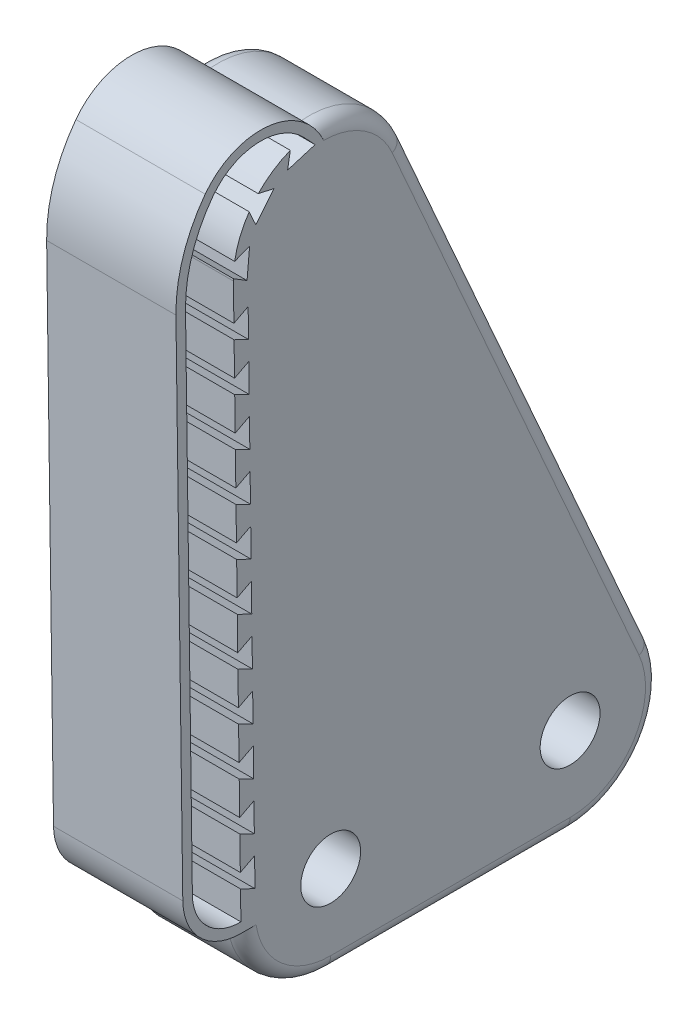
SolidWorks part; units mm, degrees
material "ABS"
ref_plane "Front" through (0, 0, 0) normal (0, 0, 1) x (1, 0, 0)
ref_plane "Top" through (0, 0, 0) normal (0, 1, 0) x (1, 0, 0)
ref_plane "Right" through (0, 0, 0) normal (1, 0, 0) x (0, 0, -1)
sketch "Sketch1" plane through (0, 0, 0) normal (1, 0, 0) x (0, 0, -1)
  line L0 (0, -4.7625) -> (12.7, -4.7625)
  line L1 (17.0561, 1.9251) -> (3.9577, 31.5642)
  line L2 (-5.1604, 29.5751) -> (-4.7621, -0.064)
  arc A0 (-4.7621, -0.064) -> (0, -4.7625) centre (0, 0) ccw
  arc A1 (12.7, -4.7625) -> (17.0561, 1.9251) centre (12.7, 0) ccw
  arc A2 (3.9577, 31.5642) -> (-5.1604, 29.5751) centre (-0.3983, 29.6391) ccw
  dimension "D1" = 4.7625
  dimension "D2" = 12.7
  dimension "D3" = 29.6418
  dimension "D4" = 90.77
extrude "Boss-Extrude1" add sketch "Sketch1" along normal blind 6.35
sketch "Sketch2" plane through (6.35, 0, 0) normal (1, 0, 0) x (0, 0, -1)
  circle A1 centre (0, 0) radius 1.5875
  circle A2 centre (12.7, 0) radius 1.5875
  dimension "D1" = 3.175
extrude "Cut-Extrude1" cut sketch "Sketch2" against normal blind 38.1
sketch "Sketch3" plane through (6.35, 0, 0) normal (1, 0, 0) x (0, 0, -1)
  line L0 (-4.7826, 1.4599) -> (-4.7928, 2.2218)
  line L1 (-5.1604, 29.5751) -> (-4.7621, -0.064) construction
  line L2 (-4.7928, 2.2218) -> (-4.036, 2.613)
  line L3 (-4.036, 2.613) -> (-4.0155, 1.0891)
  line L4 (-4.0155, 1.0891) -> (-4.7826, 1.4599)
  dimension "D1" = 0.762
  dimension "D2" = 1.524
  dimension "D3" = 0.762
  dimension "D4" = 1.524
extrude "Cut-Extrude2" cut sketch "Sketch3" against normal blind 6.35
pattern_linear "LPattern1" count 11 spacing 2.54 along (0, 0.9999, 0.0134) of "Cut-Extrude2"
sketch "Sketch5" plane through (6.35, 0, 0) normal (1, 0, 0) x (0, 0, -1)
  line L0 (-2.1425, 34.0708) -> (-2.2856, 33.2309)
  line L1 (-2.2856, 33.2309) -> (-0.8274, 33.6738)
  line L2 (-0.8274, 33.6738) -> (-1.4134, 34.2922)
  line L3 (-2.1425, 34.0708) -> (-1.4134, 34.2922) construction
  arc A0 (3.9577, 31.5642) -> (-5.1604, 29.5751) centre (-0.3983, 29.6391) ccw construction
  arc A1 (-2.1425, 34.0708) -> (-1.4134, 34.2922) centre (-0.3983, 29.6391) cw
  dimension "D1" = 0.762
  dimension "D2" = 1.524
  dimension "D3" = 0.762
extrude "Cut-Extrude3" cut sketch "Sketch5" against normal blind 6.35
pattern_circular "CirPattern1" count 3 every 34 about axis through (0, 29.6391, 0.3983) along (1, 0, 0) of "Cut-Extrude3"
sketch "Sketch6" plane through (0, 0, 0) normal (1, 0, 0) x (0, 0, -1)
  line L0 (0, 0) -> (-4.7621, -0.064) construction
  line L1 (-7.336, 2.4416) -> (-7.7002, 29.541)
  line L2 (-0.8274, 33.6738) -> (-1.4134, 34.2922) construction
  line L3 (-8.2081, 29.5342) -> (-7.844, 2.4416)
  line L4 (-4.7621, -0.5992) -> (-4.7247, -0.5992)
  line L6 (-4.7826, 1.4599) -> (-4.7621, -0.064) construction
  arc A0 (-4.7621, -0.064) -> (-7.336, 2.4416) centre (-4.7962, 2.4758) cw
  arc A1 (-7.7002, 29.541) -> (-6.2491, 34.009) centre (-0.3983, 29.6391) cw
  arc A2 (3.9577, 31.5642) -> (-1.4134, 34.2922) centre (-0.3983, 29.6391) ccw construction
  arc A3 (-1.4134, 34.2922) -> (-6.2491, 34.009) centre (-3.7119, 32.114) ccw
  arc A4 (-1.4134, 34.2922) -> (-0.8213, 34.3828) centre (-0.3983, 29.6391) cw
  arc A5 (-0.8213, 34.3828) -> (-6.6561, 34.313) centre (-3.7119, 32.114) ccw
  arc A6 (-6.6561, 34.313) -> (-8.2081, 29.5342) centre (-0.3983, 29.6391) ccw
  arc A7 (-7.844, 2.4416) -> (-4.7621, -0.5992) centre (-4.7621, 2.4831) ccw
  arc A9 (-4.7621, -0.064) -> (0, -4.7625) centre (0, 0) ccw construction
  arc A10 (-4.7621, -0.064) -> (-4.7247, -0.5992) centre (0, 0) ccw
  dimension "D1" = 2.54
  dimension "D2" = 0.508
extrude "Boss-Extrude2" add sketch "Sketch6" along normal blind 6.35
sketch "Sketch7" plane through (0, 0, 0) normal (-1, 0, 0) x (0, 0, 1)
  line L0 (3.8905, 29.5922) -> (3.4848, -0.5992)
  line L1 (4.0155, 1.0891) -> (4.036, 2.613) construction
  line L2 (4.7621, -0.5992) -> (3.4848, -0.5992)
  line L3 (7.844, 2.4416) -> (8.2081, 29.5342)
  line L4 (0.8213, 34.3828) -> (-0.2014, 33.0797)
  arc A0 (4.7621, -0.5992) -> (7.844, 2.4416) centre (4.7621, 2.4831) ccw
  arc A1 (8.2081, 29.5342) -> (6.6561, 34.313) centre (0.3983, 29.6391) ccw
  arc A2 (6.6561, 34.313) -> (0.8213, 34.3828) centre (3.7119, 32.114) ccw
  arc A3 (-0.2014, 33.0797) -> (3.8905, 29.5922) centre (0.3983, 29.6391) cw
  dimension "D1" = 0.508
extrude "Boss-Extrude3" add sketch "Sketch7" along normal blind 0.508
fillet "Fillet3" radius 0.762 10 edges at (0, -3.5732, 3.1486) (6.35, -3.5732, 3.1486) (0, -4.7625, -6.35) (6.35, -4.7625, -6.35) (6.35, 33.7413, -2.0211) (0, 33.7413, -2.0211) (0, 16.7446, -10.5069) (6.35, 16.7446, -10.5069) (0, -2.5993, -16.6906) (6.35, -2.5993, -16.6906)
